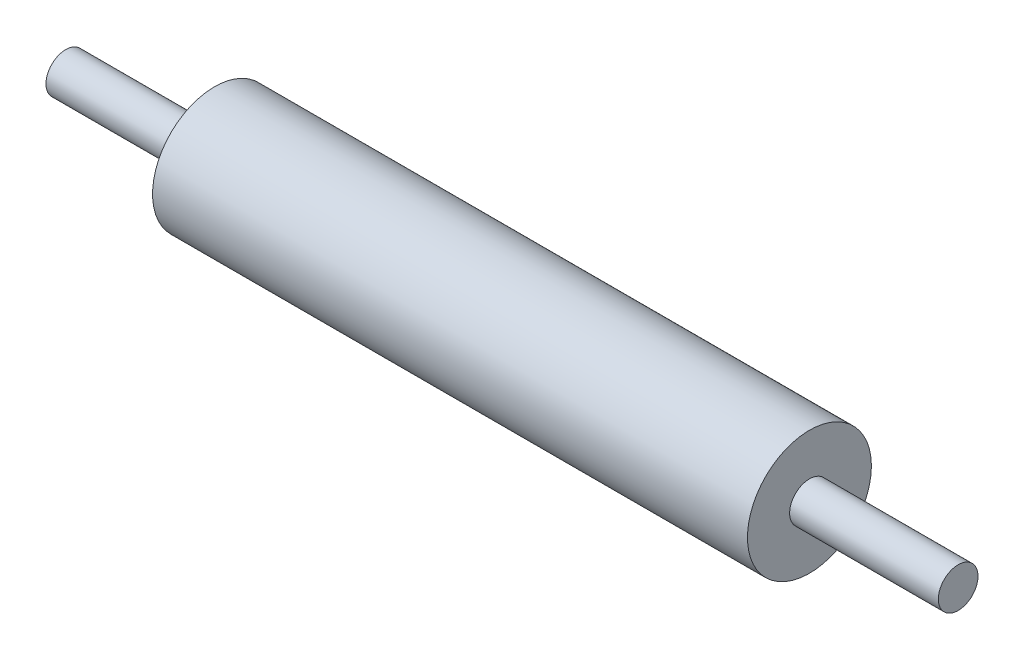
SolidWorks part; units mm, degrees
ref_plane "Front Plane" through (0, 0, 0) normal (0, 0, 1) x (1, 0, 0)
ref_plane "Top Plane" through (0, 0, 0) normal (0, 1, 0) x (1, 0, 0)
ref_plane "Right Plane" through (0, 0, 0) normal (1, 0, 0) x (0, 0, -1)
sketch "SK Fuse holder body" plane through (0, 0, 0) normal (1, 0, 0) x (0, 0, -1)
  circle A0 centre (0, 0) radius 5
extrude "Fuse holder body" add sketch "SK Fuse holder body" along normal blind 48 separate body
sketch "SK Lead in" plane through (0, 0, 0) normal (1, 0, 0) x (0, 0, -1)
  circle A0 centre (0, 0) radius 1.6
extrude "Lead in" add sketch "SK Lead in" along normal blind 12 from offset 12 separate body
sketch "SK Lead out" plane through (0, 0, 0) normal (1, 0, 0) x (0, 0, -1)
  circle A0 centre (0, 0) radius 1.6
extrude "Lead out" add sketch "SK Lead out" along normal blind 12 from offset 48 separate body
